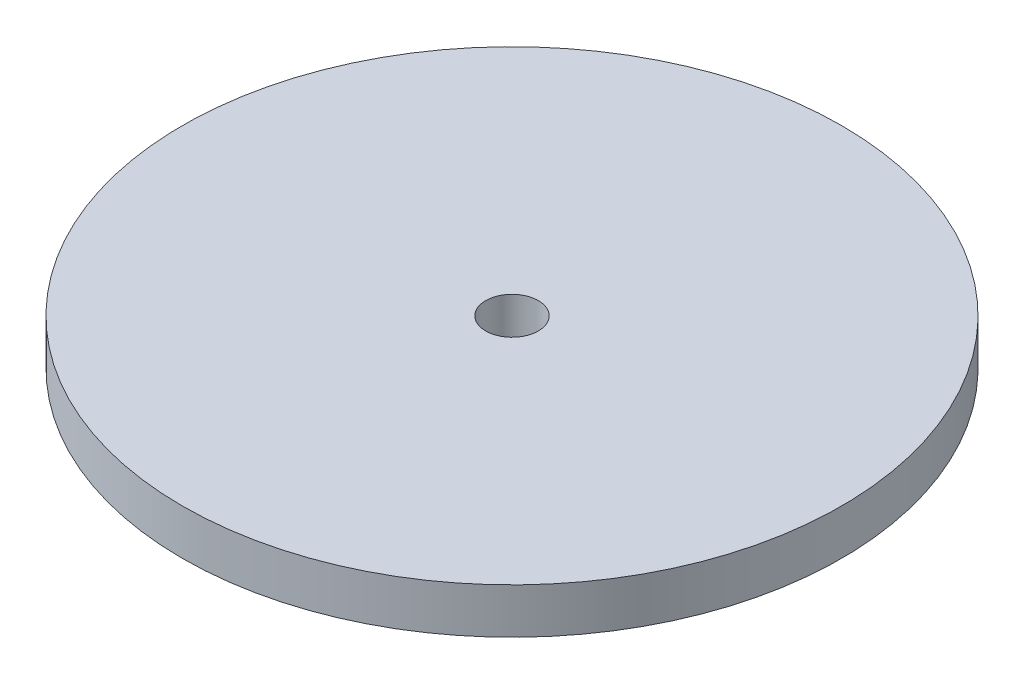
SolidWorks part; units mm, degrees
ref_plane "Front Plane" through (0, 0, 0) normal (0, 0, 1) x (1, 0, 0)
ref_plane "Top Plane" through (0, 0, 0) normal (0, 1, 0) x (1, 0, 0)
ref_plane "Right Plane" through (0, 0, 0) normal (1, 0, 0) x (0, 0, -1)
sketch "Sketch1" plane through (0, 0, 0) normal (0, 1, 0) x (1, 0, 0)
  circle A0 centre (0, 0) radius 36.3
  circle A2 centre (0, 0) radius 2.9
  dimension "D1" = 72.6
  dimension "D2" = 5.8
extrude "Boss-Extrude1" add sketch "Sketch1" along normal blind 5
